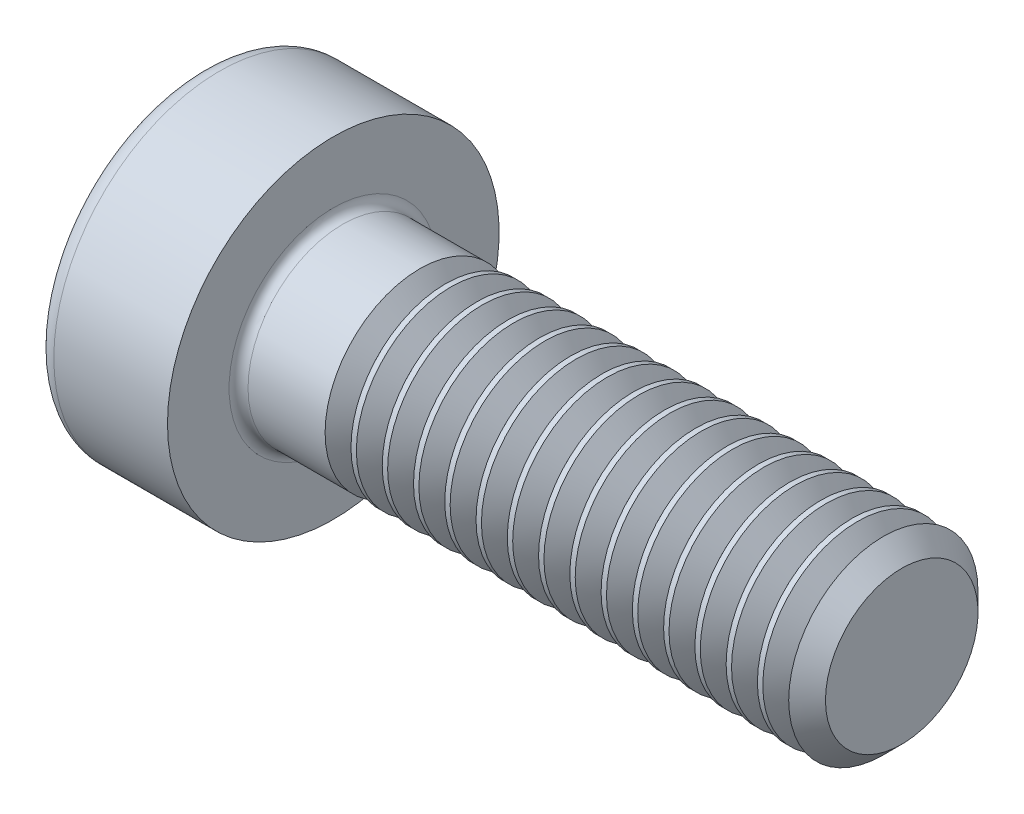
SolidWorks part; units mm, degrees
revolve "Base-Revolve" add sketch "BodySke"
sketch "BodySke" plane through (0, 0, 0) normal (0, 0, 1) x (1, 0, 0)
  line L0 (0, 0) -> (0, 3.5)
  line L1 (0, 3.5) -> (2.8, 3.5)
  line L2 (2.8, 3.5) -> (2.8, 2)
  line L3 (2.8, 2) -> (14.41, 2)
  line L4 (14.8, 1.61) -> (14.8, 0)
  line L5 (14.8, 0) -> (0, 0)
  line L6 (-31.75, 0) -> (127, 0) construction
  line L8 (14.8, 1.61) -> (14.41, 2)
  line L10 (14.8, -1.61) -> (14.41, -2) construction
  line L11 (3.5, 4.525) -> (3.5, -1.825) construction
  line L12 (4.9, 4.525) -> (4.9, -1.825) construction
  line L13 (-45.2, 4.525) -> (-45.2, -1.825) construction
  dimension "Head_ht" = 2.8
  dimension "Length" = 12
  dimension "Body_ch_ang" = 45
  dimension "Diameter" = 4
  dimension "Minor_dia" = 3.22
  dimension "Advance" = 0.7
  dimension "Thread_nom" = 9.9
  dimension "Thread_length" = 60
  dimension "Head_dia" = 7
cosmetic thread "ThreadCosmetic" [suppressed]
fillet "Fillet1" radius 0.2 1 edges at (2.8, 0, 2)
fillet "Fillet2" radius 0.4 1 edges at (0, 0, 3.5)
ref_plane "Plane1" through (0, 0, 0) normal (0, 0, 1) x (1, 0, 0)
ref_plane "Plane2" through (0, 0, 0) normal (0, 1, 0) x (1, 0, 0)
ref_plane "Plane3" through (0, 0, 0) normal (1, 0, 0) x (0, 0, -1)
sketch "Sketch2" plane through (0, 0, 0) normal (0, 0, 1) x (1, 0, 0)
  line L0 (0, 1.25) -> (2.3, 1.25)
  line L1 (2.3, 1.25) -> (3.0217, 0)
  line L2 (-31.75, 0) -> (127, 0) construction
  line L3 (3.0217, 0) -> (0, 0)
  line L4 (0, 0) -> (0, 1.25)
  line L6 (0, 0) -> (47.625, 0) construction
  dimension "D1" = 1.25
  dimension "D2" = 60
  dimension "Depth" = 2.3
revolve "Hex-PreBroach" cut sketch "Sketch2" angle 360 about L6
sketch "Sketch3" plane through (0, 0, 0) normal (-1, 0, 0) x (0, 0.5, 0.866)
  line L0 (0.7217, 1.25) -> (-0.7217, 1.25)
  line L1 (-0.7217, 1.25) -> (-1.4434, 0)
  line L2 (0.7217, 1.25) -> (1.4434, 0)
  line L3 (0.7217, -1.25) -> (1.4434, 0)
  line L4 (0.7217, -1.25) -> (-0.7217, -1.25)
  line L5 (-0.7217, -1.25) -> (-1.4434, 0)
  dimension "D1" = 1.25
  dimension "D2" = 1.25
  dimension "Hex_size" = 2.5
extrude "Hex" cut sketch "Sketch3" against normal blind 2.3
sketch "ThdSchSke" plane through (0, 0, 0) normal (0, 0, 1) x (1, 0, 0)
  line L0 (4.9, -1.61) -> (4.6269, -2)
  line L1 (4.9, -1.61) -> (5.1731, -2)
  line L2 (5.1731, -2) -> (5.1731, -2.5)
  line L3 (-3.175, 0) -> (5.1513, 0) construction
  line L4 (0, 3.1) -> (0, -3.1) construction
  line L5 (5.1731, -2.5) -> (4.6269, -2.5)
  line L6 (4.6269, -2.5) -> (4.6269, -2)
  dimension "Thread_minor" = 3.22
  dimension "Diameter" = 4
  dimension "Start" = 4.9
revolve "ThreadSchematic" cut sketch "ThdSchSke" angle 360 about L3
pattern_linear "ThdSchPat" count 15 spacing 0.66 along (1, 0, 0) of "ThreadSchematic"
equation "\"D2@Sketch3\" = \"Hex_size@Sketch3\" / 2"
equation "\"D1@Sketch3\" = \"Hex_size@Sketch3\" / 2"
equation "\"D1@Sketch2\" = \"Hex_size@Sketch3\" / 2"
equation "\"Thread_minor@ThreadCosmetic\"  =  \"Minor_dia@BodySke\""
equation "\"Depth@Sketch2\" =  \"Key_eng@Hex\""
equation "\"Thread_length@ThreadCosmetic\" = ((sgn( (\"Length@BodySke\" - \"Advance@BodySke\" * 3.0) - \"Thread_nom@BodySke\" )-1)*( (\"Length@BodySke\" - \"Advance@BodySke\" * 3.0) - \"Thread_nom@BodySke\" ))/-2+ \"Thread_nom@BodySke\""
equation "\"Thread_minor@ThdSchSke\" = \"Minor_dia@BodySke\""
equation "\"Diameter@ThdSchSke\" = \"Diameter@BodySke\""
equation "\"Overcut@ThdSchSke\" = \"Diameter@BodySke\" * 1.25"
equation "\"Start@ThdSchSke\" = \"Head_ht@BodySke\" + \"Length@BodySke\" - \"Thread_length@ThreadCosmetic\"  '---Non-countersunk---"
equation "\"Num_threads@ThdSchPat\" = int( \"Thread_length@ThreadCosmetic\" / \"Advance@BodySke\" + 0.999 )  + 1"
equation "\"Advance@ThdSchPat\" = \"Thread_length@ThreadCosmetic\" /  (\"Num_threads@ThdSchPat\" - 1) 'relax it"
equation "\"Num_threads@ThdSchPat\" = \"Num_threads@ThdSchPat\" - sgn( \"Num_threads@ThdSchPat\" - 1) '---chamfered tips only---"
